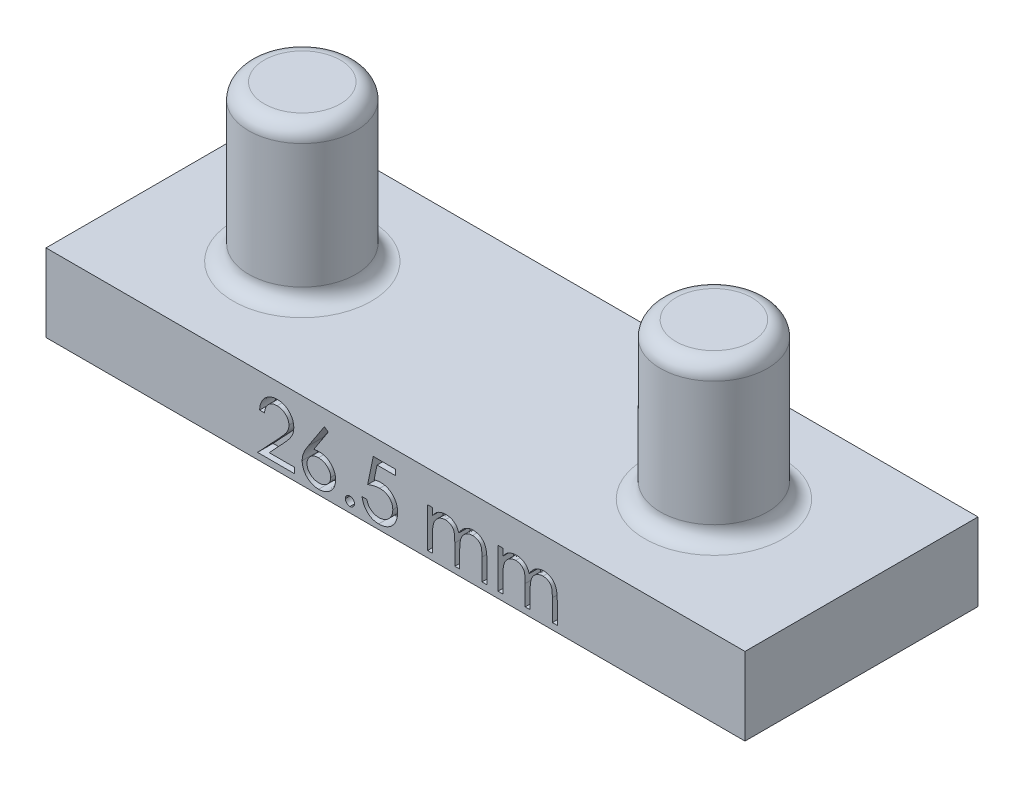
SolidWorks part; units mm, degrees
ref_plane "Front Plane" through (0, 0, 0) normal (0, 0, 1) x (1, 0, 0)
ref_plane "Top Plane" through (0, 0, 0) normal (0, 1, 0) x (1, 0, 0)
ref_plane "Right Plane" through (0, 0, 0) normal (1, 0, 0) x (0, 0, -1)
sketch "Sketch1" plane through (0, 0, 0) normal (0, 1, 0) x (1, 0, 0)
  circle A0 centre (-41.8213, 3.1021) radius 3.4487
  circle A1 centre (-15.3213, 3.1021) radius 3.4487
  dimension "D1" = 26.5
extrude "Boss-Extrude1" add sketch "Sketch1" along normal blind 10
sketch "Sketch2" plane through (0, 0, 0) normal (0, -1, 0) x (1, 0, 0)
  line L1 (-50.8213, 4.3979) -> (-5.8213, 4.3979)
  line L2 (-50.8213, 4.3979) -> (-50.8213, -10.6021)
  line L3 (-50.8213, -10.6021) -> (-5.8213, -10.6021)
  line L4 (-5.8213, 4.3979) -> (-5.8213, -10.6021)
  circle A0 centre (-41.8213, -3.1021) radius 3.4487 construction
  dimension "D1" = 45
  dimension "D2" = 15
  dimension "D3" = 7.5
  dimension "D4" = 9
extrude "Boss-Extrude2" add sketch "Sketch2" along normal blind 5
sketch "Sketch3" plane through (0, 0, 4.3979) normal (0, 0, 1) x (1, 0, 0)
  line L0 (-7.1347, -4.5918) -> (-47.7505, -4.5918) construction
  text T0 "26.5 mm"
extrude "Cut-Extrude1" cut sketch "Sketch3" against normal blind 1
fillet "Fillet1" radius 1 4 edges at (-41.8213, 0, 0.3466) (-15.3213, 0, -6.5508) (-15.3213, 10, 0.3466) (-41.8213, 10, 0.3466)
